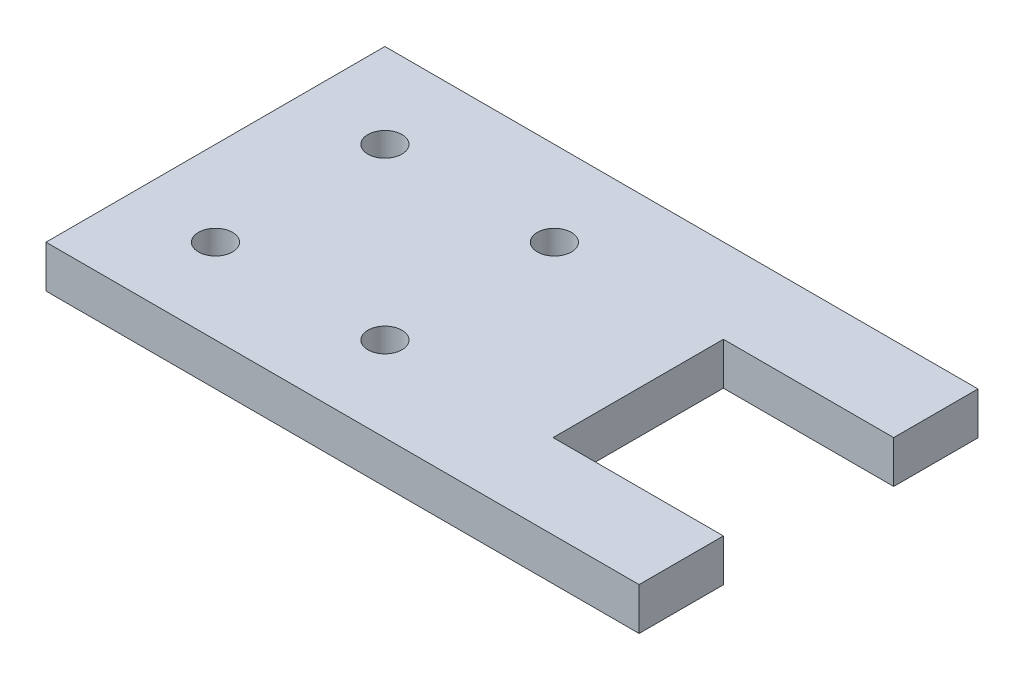
SolidWorks part; units mm, degrees
material "6061-T6 (SS)"
ref_plane "Front Plane" through (0, 0, 0) normal (0, 0, 1) x (1, 0, 0)
ref_plane "Top Plane" through (0, 0, 0) normal (0, 1, 0) x (1, 0, 0)
ref_plane "Right Plane" through (0, 0, 0) normal (1, 0, 0) x (0, 0, -1)
sketch "Sketch1" plane through (0, 0, 0) normal (0, 1, 0) x (1, 0, 0)
  line L0 (31.75, 25.4) -> (57.15, 25.4)
  line L1 (-31.75, -25.4) -> (31.75, -25.4)
  line L2 (-31.75, -25.4) -> (-31.75, 25.4)
  line L3 (-31.75, 25.4) -> (31.75, 25.4)
  line L5 (-31.75, -25.4) -> (31.75, 25.4) construction
  line L6 (-31.75, 25.4) -> (31.75, -25.4) construction
  line L7 (57.15, 25.4) -> (57.15, -25.4)
  line L8 (57.15, -25.4) -> (31.75, -25.4)
  point P0 (0, 0)
  dimension "D1" = 63.5
  dimension "D2" = 50.8
  dimension "D3" = 25.4
extrude "Boss-Extrude1" add sketch "Sketch1" along normal blind 6.35
sketch "Sketch2" plane through (0, 6.35, 0) normal (0, 1, 0) x (1, 0, 0)
  line L4 (57.15, 25.4) -> (-31.75, 25.4) construction
  line L5 (-31.75, -25.4) -> (57.15, -25.4) construction
  line L7 (19.05, 25.4) -> (19.05, -25.4) construction
  line L8 (-31.75, 25.4) -> (-31.75, -25.4) construction
  dimension "D1" = 50.8
hole_wizard "#10 Clearance Hole1" positions "Sketch3" profile "Sketch4" hole size "#10" standard "ANSI Inch" end condition through all
sketch "Sketch3" plane through (0, 6.35, 0) normal (0, 1, 0) x (1, 0, 0)
  line L4 (-19.05, 25.4) -> (-19.05, -25.4) construction
  line L5 (57.15, 25.4) -> (-31.75, 25.4) construction
  line L6 (-31.75, -25.4) -> (57.15, -25.4) construction
  line L8 (6.35, 25.4) -> (6.35, -25.4) construction
  line L9 (-31.75, 25.4) -> (-31.75, -25.4) construction
  line L11 (-31.75, 12.7) -> (19.05, 12.7) construction
  line L13 (-31.75, -12.7) -> (19.05, -12.7) construction
  point P0 (-19.05, 12.7)
  point P2 (6.35, 12.7)
  point P4 (6.35, -12.7)
  point P6 (-19.05, -12.7)
  dimension "D1" = 12.7
  dimension "D2" = 38.1
  dimension "D3" = 12.7
  dimension "D4" = 12.7
  dimension "D5" = 50.8
  dimension "D6" = 50.8
sketch "Sketch4" plane through (-19.05, 6.35, -12.7) normal (1, 0, 0) x (0, 0, 1)
  line L0 (0, 0) -> (0, 6.35)
  line L1 (0, 6.35) -> (2.5527, 6.35)
  line L2 (2.5527, 6.35) -> (2.5527, 0)
  line L5 (2.5527, 0) -> (0, 0)
  line L11 (0, -6.35) -> (0, 107.95) construction
  dimension "Thru Hole Dia." = 5.1054
  dimension "Thru Hole Depth" = 6.35
sketch "Sketch5" plane through (0, 6.35, 0) normal (0, 1, 0) x (1, 0, 0)
  line L1 (57.15, -25.4) -> (57.15, 25.4) construction
  line L2 (31.623, -12.7635) -> (57.15, -12.7635)
  line L4 (31.623, -12.7635) -> (31.623, 12.7635)
  line L5 (31.623, 12.7635) -> (57.15, 12.7635)
  line L6 (57.15, -12.7635) -> (57.15, 12.7635)
  line L7 (31.623, -12.7635) -> (57.15, 12.7635) construction
  line L8 (31.623, 12.7635) -> (57.15, -12.7635) construction
  line L13 (57.15, 12.7635) -> (57.15, 25.4) construction
  line L14 (57.15, -12.7635) -> (57.15, -25.4) construction
  dimension "D3" = 25.527
extrude "Cut-Extrude1" cut sketch "Sketch5" against normal through all
